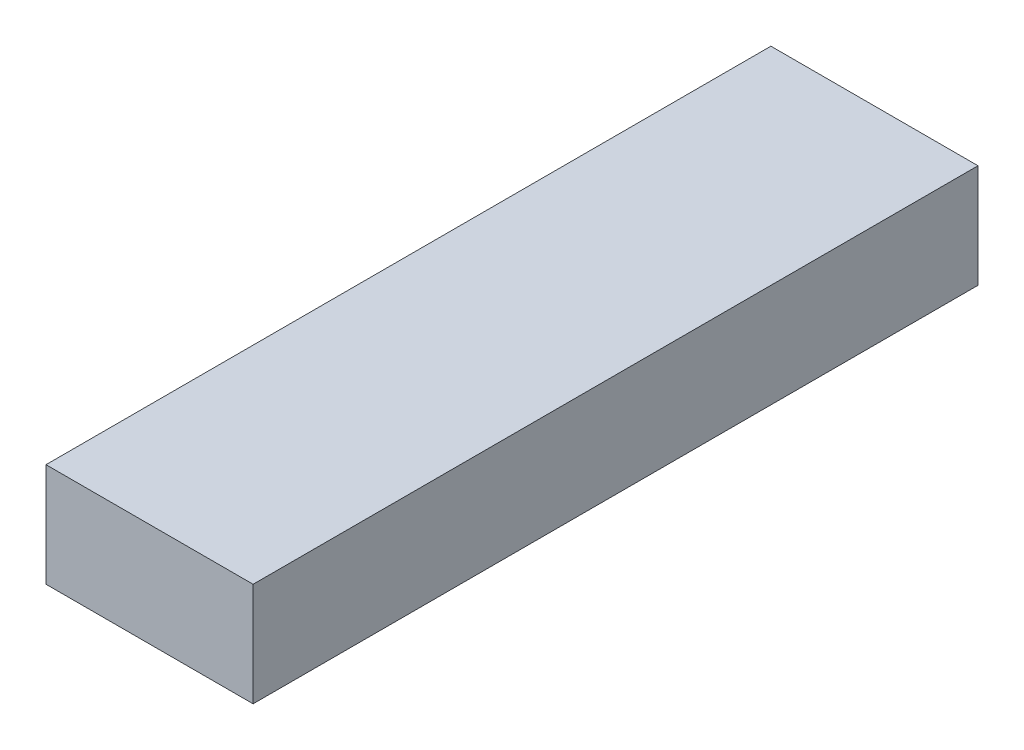
SolidWorks part; units mm, degrees
ref_plane "Front Plane" through (0, 0, 0) normal (0, 0, 1) x (1, 0, 0)
ref_plane "Top Plane" through (0, 0, 0) normal (0, 1, 0) x (1, 0, 0)
ref_plane "Right Plane" through (0, 0, 0) normal (1, 0, 0) x (0, 0, -1)
sketch "Sketch1" plane through (0, 0, 0) normal (0, 1, 0) x (1, 0, 0)
  line L1 (-10, -35) -> (10, -35)
  line L2 (-10, -35) -> (-10, 35)
  line L3 (-10, 35) -> (10, 35)
  line L4 (10, -35) -> (10, 35)
  line L5 (0, 35) -> (0, -35) construction
  line L6 (-10, 0) -> (10, 0) construction
  point P0 (0, 0)
  dimension "D1" = 20
  dimension "D2" = 70
extrude "Boss-Extrude1" add sketch "Sketch1" along normal blind 10
